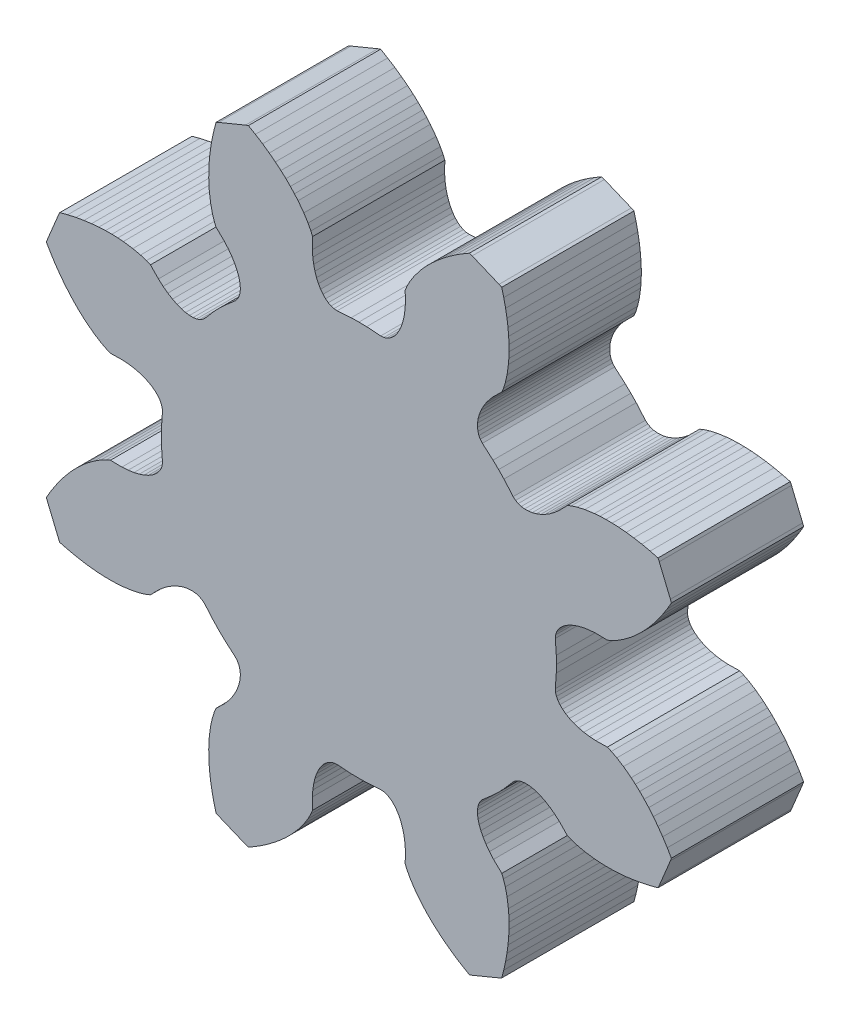
SolidWorks part; units mm, degrees
ref_plane "Front Plane" through (0, 0, 0) normal (0, 0, 1) x (1, 0, 0)
ref_plane "Top Plane" through (0, 0, 0) normal (0, 1, 0) x (1, 0, 0)
ref_plane "Right Plane" through (0, 0, 0) normal (1, 0, 0) x (0, 0, -1)
sketch "Sketch1" plane through (0, 0, 0) normal (0, 0, 1) x (1, 0, 0)
  line L0 (-25.6921, 14.6152) -> (-25.7624, 14.9363)
  line L1 (-25.7624, 14.9363) -> (-25.816, 15.2423)
  line L2 (-25.816, 15.2423) -> (-25.8546, 15.5344)
  line L3 (-25.8546, 15.5344) -> (-25.8795, 15.8113)
  line L4 (-25.8795, 15.8113) -> (-25.892, 16.0716)
  line L5 (-25.892, 16.0716) -> (-25.8935, 16.3157)
  line L6 (-25.8935, 16.3157) -> (-25.8848, 16.5428)
  line L7 (-25.8848, 16.5428) -> (-25.8699, 16.7524)
  line L8 (-25.8699, 16.7524) -> (-25.8175, 17.1189)
  line L9 (-25.8175, 17.1189) -> (-25.7512, 17.4153)
  line L10 (-25.7512, 17.4153) -> (-25.6796, 17.6414)
  line L11 (-25.6796, 17.6414) -> (-25.6164, 17.7971)
  line L12 (-25.6164, 17.7971) -> (-25.2994, 18.1029)
  line L13 (-25.2994, 18.1029) -> (-25.1424, 18.2835)
  line L14 (-25.1424, 18.2835) -> (-25.0085, 18.4641)
  line L15 (-25.0085, 18.4641) -> (-24.8983, 18.6434)
  line L16 (-24.8983, 18.6434) -> (-24.8114, 18.8169)
  line L17 (-24.8114, 18.8169) -> (-24.7469, 18.9835)
  line L18 (-24.7469, 18.9835) -> (-24.7053, 19.1445)
  line L19 (-24.7053, 19.1445) -> (-24.6834, 19.2949)
  line L20 (-24.6834, 19.2949) -> (-24.6819, 19.4371)
  line L21 (-24.6819, 19.4371) -> (-24.7015, 19.5652)
  line L22 (-24.7015, 19.5652) -> (-24.737, 19.681)
  line L23 (-24.737, 19.681) -> (-24.7909, 19.7813)
  line L24 (-24.7909, 19.7813) -> (-24.8706, 19.8766)
  line L25 (-24.8706, 19.8766) -> (-25.2785, 20.2309)
  line L26 (-25.2785, 20.2309) -> (-25.4922, 20.4361)
  line L27 (-25.4922, 20.4361) -> (-25.6976, 20.6495)
  line L28 (-25.6976, 20.6495) -> (-26.0517, 21.0589)
  line L29 (-26.0517, 21.0589) -> (-26.1467, 21.1374)
  line L30 (-26.1467, 21.1374) -> (-26.2476, 21.191)
  line L31 (-26.2476, 21.191) -> (-26.3634, 21.2286)
  line L32 (-26.3634, 21.2286) -> (-26.4927, 21.2461)
  line L33 (-26.4927, 21.2461) -> (-26.6331, 21.2451)
  line L34 (-26.6331, 21.2451) -> (-26.7848, 21.2243)
  line L35 (-26.7848, 21.2243) -> (-26.9445, 21.1816)
  line L36 (-26.9445, 21.1816) -> (-27.1129, 21.1166)
  line L37 (-27.1129, 21.1166) -> (-27.2864, 21.03)
  line L38 (-27.2864, 21.03) -> (-27.4642, 20.9197)
  line L39 (-27.4642, 20.9197) -> (-27.6448, 20.7874)
  line L40 (-27.6448, 20.7874) -> (-27.8267, 20.6287)
  line L41 (-27.8267, 20.6287) -> (-28.1325, 20.3134)
  line L42 (-28.1325, 20.3134) -> (-28.2884, 20.2484)
  line L43 (-28.2884, 20.2484) -> (-28.5143, 20.1783)
  line L44 (-28.5143, 20.1783) -> (-28.8091, 20.111)
  line L45 (-28.8091, 20.111) -> (-29.1757, 20.0597)
  line L46 (-29.1757, 20.0597) -> (-29.3852, 20.0432)
  line L47 (-29.3852, 20.0432) -> (-29.6141, 20.0351)
  line L48 (-29.6141, 20.0351) -> (-29.8579, 20.0363)
  line L49 (-29.8579, 20.0363) -> (-30.1167, 20.0488)
  line L50 (-30.1167, 20.0488) -> (-30.3951, 20.0734)
  line L51 (-30.3951, 20.0734) -> (-30.6862, 20.1138)
  line L52 (-30.6862, 20.1138) -> (-30.9935, 20.1674)
  line L53 (-30.9935, 20.1674) -> (-31.3131, 20.2375)
  line L54 (-31.3131, 20.2375) -> (-31.6148, 20.3162)
  line L55 (-31.6148, 20.3162) -> (-31.6644, 20.4181)
  line L56 (-31.6644, 20.4181) -> (-32.0931, 21.4529)
  line L57 (-32.0931, 21.4529) -> (-32.1302, 21.5575)
  line L58 (-32.1302, 21.5575) -> (-31.9717, 21.8278)
  line L59 (-31.9717, 21.8278) -> (-31.7954, 22.1034)
  line L60 (-31.7954, 22.1034) -> (-31.6161, 22.3584)
  line L61 (-31.6161, 22.3584) -> (-31.4383, 22.5926)
  line L62 (-31.4383, 22.5926) -> (-31.2595, 22.8062)
  line L63 (-31.2595, 22.8062) -> (-31.0845, 22.999)
  line L64 (-31.0845, 22.999) -> (-30.9133, 23.1727)
  line L65 (-30.9133, 23.1727) -> (-30.7467, 23.3272)
  line L66 (-30.7467, 23.3272) -> (-30.5866, 23.4651)
  line L67 (-30.5866, 23.4651) -> (-30.2907, 23.6881)
  line L68 (-30.2907, 23.6881) -> (-30.0342, 23.8494)
  line L69 (-30.0342, 23.8494) -> (-29.8246, 23.9583)
  line L70 (-29.8246, 23.9583) -> (-29.6692, 24.0231)
  line L71 (-29.6692, 24.0231) -> (-29.2295, 24.0163)
  line L72 (-29.2295, 24.0163) -> (-28.9897, 24.0328)
  line L73 (-28.9897, 24.0328) -> (-28.7665, 24.0658)
  line L74 (-28.7665, 24.0658) -> (-28.5638, 24.1138)
  line L75 (-28.5638, 24.1138) -> (-28.3794, 24.176)
  line L76 (-28.3794, 24.176) -> (-28.2153, 24.2489)
  line L77 (-28.2153, 24.2489) -> (-28.0718, 24.332)
  line L78 (-28.0718, 24.332) -> (-27.9494, 24.4239)
  line L79 (-27.9494, 24.4239) -> (-27.8503, 24.5235)
  line L80 (-27.8503, 24.5235) -> (-27.7716, 24.6264)
  line L81 (-27.7716, 24.6264) -> (-27.7152, 24.7341)
  line L82 (-27.7152, 24.7341) -> (-27.6819, 24.8446)
  line L83 (-27.6819, 24.8446) -> (-27.671, 24.967)
  line L84 (-27.671, 24.967) -> (-27.7096, 25.506)
  line L85 (-27.7096, 25.506) -> (-27.7152, 25.8021)
  line L86 (-27.7152, 25.8021) -> (-27.7096, 26.0996)
  line L87 (-27.7096, 26.0996) -> (-27.671, 26.6388)
  line L88 (-27.671, 26.6388) -> (-27.6819, 26.7612)
  line L89 (-27.6819, 26.7612) -> (-27.7152, 26.8715)
  line L90 (-27.7152, 26.8715) -> (-27.7716, 26.9787)
  line L91 (-27.7716, 26.9787) -> (-27.8503, 27.082)
  line L92 (-27.8503, 27.082) -> (-27.9494, 27.1816)
  line L93 (-27.9494, 27.1816) -> (-28.0718, 27.2723)
  line L94 (-28.0718, 27.2723) -> (-28.2153, 27.3566)
  line L95 (-28.2153, 27.3566) -> (-28.3794, 27.4295)
  line L96 (-28.3794, 27.4295) -> (-28.5638, 27.4917)
  line L97 (-28.5638, 27.4917) -> (-28.7665, 27.5397)
  line L98 (-28.7665, 27.5397) -> (-28.9897, 27.5728)
  line L99 (-28.9897, 27.5728) -> (-29.2295, 27.5895)
  line L100 (-29.2295, 27.5895) -> (-29.6692, 27.5824)
  line L101 (-29.6692, 27.5824) -> (-29.8246, 27.6472)
  line L102 (-29.8246, 27.6472) -> (-30.0342, 27.7564)
  line L103 (-30.0342, 27.7564) -> (-30.2907, 27.9174)
  line L104 (-30.2907, 27.9174) -> (-30.5866, 28.1405)
  line L105 (-30.5866, 28.1405) -> (-30.7467, 28.2784)
  line L106 (-30.7467, 28.2784) -> (-30.9133, 28.4328)
  line L107 (-30.9133, 28.4328) -> (-31.0845, 28.6065)
  line L108 (-31.0845, 28.6065) -> (-31.2595, 28.7993)
  line L109 (-31.2595, 28.7993) -> (-31.4383, 29.0129)
  line L110 (-31.4383, 29.0129) -> (-31.6161, 29.2471)
  line L111 (-31.6161, 29.2471) -> (-31.7954, 29.5021)
  line L112 (-31.7954, 29.5021) -> (-31.9717, 29.7777)
  line L113 (-31.9717, 29.7777) -> (-32.1302, 30.048)
  line L114 (-32.1302, 30.048) -> (-32.0931, 30.1537)
  line L115 (-32.0931, 30.1537) -> (-31.6644, 31.1887)
  line L116 (-31.6644, 31.1887) -> (-31.6148, 31.2893)
  line L117 (-31.6148, 31.2893) -> (-31.3131, 31.368)
  line L118 (-31.3131, 31.368) -> (-30.9935, 31.4381)
  line L119 (-30.9935, 31.4381) -> (-30.6862, 31.492)
  line L120 (-30.6862, 31.492) -> (-30.3951, 31.5306)
  line L121 (-30.3951, 31.5306) -> (-30.1167, 31.5568)
  line L122 (-30.1167, 31.5568) -> (-29.8579, 31.5692)
  line L123 (-29.8579, 31.5692) -> (-29.6141, 31.5705)
  line L124 (-29.6141, 31.5705) -> (-29.3852, 31.5623)
  line L125 (-29.3852, 31.5623) -> (-29.1757, 31.5458)
  line L126 (-29.1757, 31.5458) -> (-28.8091, 31.4948)
  line L127 (-28.8091, 31.4948) -> (-28.5143, 31.4272)
  line L128 (-28.5143, 31.4272) -> (-28.2884, 31.3571)
  line L129 (-28.2884, 31.3571) -> (-28.1325, 31.2921)
  line L130 (-28.1325, 31.2921) -> (-27.8267, 30.9764)
  line L131 (-27.8267, 30.9764) -> (-27.6448, 30.8181)
  line L132 (-27.6448, 30.8181) -> (-27.4642, 30.6843)
  line L133 (-27.4642, 30.6843) -> (-27.2864, 30.5758)
  line L134 (-27.2864, 30.5758) -> (-27.1129, 30.4889)
  line L135 (-27.1129, 30.4889) -> (-26.9445, 30.4239)
  line L136 (-26.9445, 30.4239) -> (-26.7848, 30.3812)
  line L137 (-26.7848, 30.3812) -> (-26.6331, 30.3604)
  line L138 (-26.6331, 30.3604) -> (-26.4927, 30.3591)
  line L139 (-26.4927, 30.3591) -> (-26.3634, 30.3772)
  line L140 (-26.3634, 30.3772) -> (-26.2476, 30.4145)
  line L141 (-26.2476, 30.4145) -> (-26.1467, 30.4681)
  line L142 (-26.1467, 30.4681) -> (-26.0517, 30.5469)
  line L143 (-26.0517, 30.5469) -> (-25.6976, 30.956)
  line L144 (-25.6976, 30.956) -> (-25.4922, 31.1694)
  line L145 (-25.4922, 31.1694) -> (-25.2785, 31.3746)
  line L146 (-25.2785, 31.3746) -> (-24.8706, 31.729)
  line L147 (-24.8706, 31.729) -> (-24.7909, 31.8242)
  line L148 (-24.7909, 31.8242) -> (-24.737, 31.9248)
  line L149 (-24.737, 31.9248) -> (-24.7015, 32.0404)
  line L150 (-24.7015, 32.0404) -> (-24.6819, 32.1684)
  line L151 (-24.6819, 32.1684) -> (-24.6834, 32.3094)
  line L152 (-24.6834, 32.3094) -> (-24.7053, 32.461)
  line L153 (-24.7053, 32.461) -> (-24.7469, 32.622)
  line L154 (-24.7469, 32.622) -> (-24.8114, 32.7887)
  line L155 (-24.8114, 32.7887) -> (-24.8983, 32.9621)
  line L156 (-24.8983, 32.9621) -> (-25.0085, 33.1399)
  line L157 (-25.0085, 33.1399) -> (-25.1424, 33.3221)
  line L158 (-25.1424, 33.3221) -> (-25.2994, 33.5026)
  line L159 (-25.2994, 33.5026) -> (-25.6164, 33.8085)
  line L160 (-25.6164, 33.8085) -> (-25.6796, 33.9642)
  line L161 (-25.6796, 33.9642) -> (-25.7512, 34.1902)
  line L162 (-25.7512, 34.1902) -> (-25.8175, 34.4851)
  line L163 (-25.8175, 34.4851) -> (-25.8699, 34.8532)
  line L164 (-25.8699, 34.8532) -> (-25.8848, 35.0627)
  line L165 (-25.8848, 35.0627) -> (-25.8935, 35.2898)
  line L166 (-25.8935, 35.2898) -> (-25.892, 35.5336)
  line L167 (-25.892, 35.5336) -> (-25.8795, 35.7942)
  line L168 (-25.8795, 35.7942) -> (-25.8546, 36.0714)
  line L169 (-25.8546, 36.0714) -> (-25.816, 36.3635)
  line L170 (-25.816, 36.3635) -> (-25.7624, 36.6693)
  line L171 (-25.7624, 36.6693) -> (-25.6921, 36.9903)
  line L172 (-25.6921, 36.9903) -> (-25.6123, 37.2923)
  line L173 (-25.6123, 37.2923) -> (-25.5117, 37.3406)
  line L174 (-25.5117, 37.3406) -> (-24.4767, 37.7688)
  line L175 (-24.4767, 37.7688) -> (-24.3705, 37.8062)
  line L176 (-24.3705, 37.8062) -> (-24.102, 37.6492)
  line L177 (-24.102, 37.6492) -> (-23.8247, 37.4729)
  line L178 (-23.8247, 37.4729) -> (-23.5699, 37.2936)
  line L179 (-23.5699, 37.2936) -> (-23.3372, 37.1145)
  line L180 (-23.3372, 37.1145) -> (-23.1218, 36.9367)
  line L181 (-23.1218, 36.9367) -> (-22.929, 36.7617)
  line L182 (-22.929, 36.7617) -> (-22.7568, 36.5895)
  line L183 (-22.7568, 36.5895) -> (-22.6014, 36.4226)
  line L184 (-22.6014, 36.4226) -> (-22.4632, 36.2629)
  line L185 (-22.4632, 36.2629) -> (-22.2415, 35.968)
  line L186 (-22.2415, 35.968) -> (-22.0789, 35.7114)
  line L187 (-22.0789, 35.7114) -> (-21.9702, 35.5009)
  line L188 (-21.9702, 35.5009) -> (-21.9052, 35.3464)
  line L189 (-21.9052, 35.3464) -> (-21.9123, 34.9052)
  line L190 (-21.9123, 34.9052) -> (-21.8958, 34.6657)
  line L191 (-21.8958, 34.6657) -> (-21.8625, 34.444)
  line L192 (-21.8625, 34.444) -> (-21.8142, 34.2398)
  line L193 (-21.8142, 34.2398) -> (-21.752, 34.0566)
  line L194 (-21.752, 34.0566) -> (-21.6791, 33.8925)
  line L195 (-21.6791, 33.8925) -> (-21.5966, 33.7493)
  line L196 (-21.5966, 33.7493) -> (-21.5041, 33.6266)
  line L197 (-21.5041, 33.6266) -> (-21.4063, 33.526)
  line L198 (-21.4063, 33.526) -> (-21.3017, 33.4473)
  line L199 (-21.3017, 33.4473) -> (-21.194, 33.3922)
  line L200 (-21.194, 33.3922) -> (-21.0853, 33.3591)
  line L201 (-21.0853, 33.3591) -> (-20.9613, 33.3482)
  line L202 (-20.9613, 33.3482) -> (-20.4226, 33.3871)
  line L203 (-20.4226, 33.3871) -> (-20.1262, 33.3922)
  line L204 (-20.1262, 33.3922) -> (-19.8297, 33.3871)
  line L205 (-19.8297, 33.3871) -> (-19.2897, 33.3482)
  line L206 (-19.2897, 33.3482) -> (-19.1671, 33.3591)
  line L207 (-19.1671, 33.3591) -> (-19.0583, 33.3922)
  line L208 (-19.0583, 33.3922) -> (-18.9506, 33.4473)
  line L209 (-18.9506, 33.4473) -> (-18.846, 33.526)
  line L210 (-18.846, 33.526) -> (-18.7467, 33.6266)
  line L211 (-18.7467, 33.6266) -> (-18.6558, 33.7493)
  line L212 (-18.6558, 33.7493) -> (-18.5719, 33.8925)
  line L213 (-18.5719, 33.8925) -> (-18.4988, 34.0566)
  line L214 (-18.4988, 34.0566) -> (-18.4381, 34.2398)
  line L215 (-18.4381, 34.2398) -> (-18.3898, 34.444)
  line L216 (-18.3898, 34.444) -> (-18.3565, 34.6657)
  line L217 (-18.3565, 34.6657) -> (-18.339, 34.9052)
  line L218 (-18.339, 34.9052) -> (-18.3471, 35.3464)
  line L219 (-18.3471, 35.3464) -> (-18.2811, 35.5009)
  line L220 (-18.2811, 35.5009) -> (-18.1721, 35.7114)
  line L221 (-18.1721, 35.7114) -> (-18.0108, 35.968)
  line L222 (-18.0108, 35.968) -> (-17.7876, 36.2629)
  line L223 (-17.7876, 36.2629) -> (-17.6512, 36.4226)
  line L224 (-17.6512, 36.4226) -> (-17.4955, 36.5895)
  line L225 (-17.4955, 36.5895) -> (-17.322, 36.7617)
  line L226 (-17.322, 36.7617) -> (-17.129, 36.9367)
  line L227 (-17.129, 36.9367) -> (-16.9151, 37.1145)
  line L228 (-16.9151, 37.1145) -> (-16.6824, 37.2936)
  line L229 (-16.6824, 37.2936) -> (-16.4277, 37.4729)
  line L230 (-16.4277, 37.4729) -> (-16.1503, 37.6492)
  line L231 (-16.1503, 37.6492) -> (-15.8805, 37.8062)
  line L232 (-15.8805, 37.8062) -> (-15.7756, 37.7688)
  line L233 (-15.7756, 37.7688) -> (-14.7421, 37.3406)
  line L234 (-14.7421, 37.3406) -> (-14.64, 37.2923)
  line L235 (-14.64, 37.2923) -> (-14.5605, 36.9903)
  line L236 (-14.5605, 36.9903) -> (-14.4899, 36.6693)
  line L237 (-14.4899, 36.6693) -> (-14.4363, 36.3635)
  line L238 (-14.4363, 36.3635) -> (-14.3977, 36.0714)
  line L239 (-14.3977, 36.0714) -> (-14.3728, 35.7942)
  line L240 (-14.3728, 35.7942) -> (-14.3591, 35.5336)
  line L241 (-14.3591, 35.5336) -> (-14.3576, 35.2898)
  line L242 (-14.3576, 35.2898) -> (-14.3659, 35.0627)
  line L243 (-14.3659, 35.0627) -> (-14.3827, 34.8532)
  line L244 (-14.3827, 34.8532) -> (-14.4335, 34.4851)
  line L245 (-14.4335, 34.4851) -> (-14.5011, 34.1902)
  line L246 (-14.5011, 34.1902) -> (-14.5727, 33.9642)
  line L247 (-14.5727, 33.9642) -> (-14.6362, 33.8085)
  line L248 (-14.6362, 33.8085) -> (-14.9529, 33.5026)
  line L249 (-14.9529, 33.5026) -> (-15.1099, 33.3221)
  line L250 (-15.1099, 33.3221) -> (-15.2438, 33.1399)
  line L251 (-15.2438, 33.1399) -> (-15.3543, 32.9621)
  line L252 (-15.3543, 32.9621) -> (-15.4409, 32.7887)
  line L253 (-15.4409, 32.7887) -> (-15.5041, 32.622)
  line L254 (-15.5041, 32.622) -> (-15.547, 32.461)
  line L255 (-15.547, 32.461) -> (-15.5689, 32.3094)
  line L256 (-15.5689, 32.3094) -> (-15.5689, 32.1684)
  line L257 (-15.5689, 32.1684) -> (-15.5511, 32.0404)
  line L258 (-15.5511, 32.0404) -> (-15.5153, 31.9248)
  line L259 (-15.5153, 31.9248) -> (-15.4614, 31.8242)
  line L260 (-15.4614, 31.8242) -> (-15.3817, 31.729)
  line L261 (-15.3817, 31.729) -> (-14.9738, 31.3746)
  line L262 (-14.9738, 31.3746) -> (-14.7586, 31.1694)
  line L263 (-14.7586, 31.1694) -> (-14.5534, 30.956)
  line L264 (-14.5534, 30.956) -> (-14.1991, 30.5469)
  line L265 (-14.1991, 30.5469) -> (-14.1056, 30.4681)
  line L266 (-14.1056, 30.4681) -> (-14.0037, 30.4145)
  line L267 (-14.0037, 30.4145) -> (-13.8877, 30.3772)
  line L268 (-13.8877, 30.3772) -> (-13.7596, 30.3591)
  line L269 (-13.7596, 30.3591) -> (-13.6192, 30.3604)
  line L270 (-13.6192, 30.3604) -> (-13.4675, 30.3812)
  line L271 (-13.4675, 30.3812) -> (-13.3078, 30.4239)
  line L272 (-13.3078, 30.4239) -> (-13.1394, 30.4889)
  line L273 (-13.1394, 30.4889) -> (-12.9659, 30.5758)
  line L274 (-12.9659, 30.5758) -> (-12.7881, 30.6843)
  line L275 (-12.7881, 30.6843) -> (-12.6078, 30.8181)
  line L276 (-12.6078, 30.8181) -> (-12.4256, 30.9764)
  line L277 (-12.4256, 30.9764) -> (-12.1198, 31.2921)
  line L278 (-12.1198, 31.2921) -> (-11.9639, 31.3571)
  line L279 (-11.9639, 31.3571) -> (-11.7381, 31.4272)
  line L280 (-11.7381, 31.4272) -> (-11.4432, 31.4948)
  line L281 (-11.4432, 31.4948) -> (-11.0766, 31.5458)
  line L282 (-11.0766, 31.5458) -> (-10.8658, 31.5623)
  line L283 (-10.8658, 31.5623) -> (-10.6382, 31.5705)
  line L284 (-10.6382, 31.5705) -> (-10.3944, 31.5692)
  line L285 (-10.3944, 31.5692) -> (-10.1341, 31.5568)
  line L286 (-10.1341, 31.5568) -> (-9.8572, 31.5306)
  line L287 (-9.8572, 31.5306) -> (-9.5651, 31.492)
  line L288 (-9.5651, 31.492) -> (-9.2588, 31.4381)
  line L289 (-9.2588, 31.4381) -> (-8.9377, 31.368)
  line L290 (-8.9377, 31.368) -> (-8.6362, 31.2893)
  line L291 (-8.6362, 31.2893) -> (-8.588, 31.1887)
  line L292 (-8.588, 31.1887) -> (-8.1592, 30.1537)
  line L293 (-8.1592, 30.1537) -> (-8.1221, 30.048)
  line L294 (-8.1221, 30.048) -> (-8.2791, 29.7777)
  line L295 (-8.2791, 29.7777) -> (-8.4569, 29.5021)
  line L296 (-8.4569, 29.5021) -> (-8.6347, 29.2471)
  line L297 (-8.6347, 29.2471) -> (-8.814, 29.0129)
  line L298 (-8.814, 29.0129) -> (-8.9928, 28.7993)
  line L299 (-8.9928, 28.7993) -> (-9.1681, 28.6065)
  line L300 (-9.1681, 28.6065) -> (-9.339, 28.4328)
  line L301 (-9.339, 28.4328) -> (-9.5059, 28.2784)
  line L302 (-9.5059, 28.2784) -> (-9.6657, 28.1405)
  line L303 (-9.6657, 28.1405) -> (-9.9618, 27.9174)
  line L304 (-9.9618, 27.9174) -> (-10.2166, 27.7564)
  line L305 (-10.2166, 27.7564) -> (-10.4277, 27.6472)
  line L306 (-10.4277, 27.6472) -> (-10.5831, 27.5824)
  line L307 (-10.5831, 27.5824) -> (-11.0228, 27.5895)
  line L308 (-11.0228, 27.5895) -> (-11.2626, 27.5728)
  line L309 (-11.2626, 27.5728) -> (-11.4846, 27.5397)
  line L310 (-11.4846, 27.5397) -> (-11.6885, 27.4917)
  line L311 (-11.6885, 27.4917) -> (-11.8729, 27.4295)
  line L312 (-11.8729, 27.4295) -> (-12.037, 27.3566)
  line L313 (-12.037, 27.3566) -> (-12.1805, 27.2723)
  line L314 (-12.1805, 27.2723) -> (-12.3014, 27.1816)
  line L315 (-12.3014, 27.1816) -> (-12.402, 27.082)
  line L316 (-12.402, 27.082) -> (-12.4808, 26.9787)
  line L317 (-12.4808, 26.9787) -> (-12.5359, 26.8715)
  line L318 (-12.5359, 26.8715) -> (-12.5704, 26.7612)
  line L319 (-12.5704, 26.7612) -> (-12.5813, 26.6388)
  line L320 (-12.5813, 26.6388) -> (-12.5427, 26.0996)
  line L321 (-12.5427, 26.0996) -> (-12.5359, 25.8021)
  line L322 (-12.5359, 25.8021) -> (-12.5427, 25.506)
  line L323 (-12.5427, 25.506) -> (-12.5813, 24.967)
  line L324 (-12.5813, 24.967) -> (-12.5704, 24.8446)
  line L325 (-12.5704, 24.8446) -> (-12.5359, 24.7341)
  line L326 (-12.5359, 24.7341) -> (-12.4808, 24.6264)
  line L327 (-12.4808, 24.6264) -> (-12.402, 24.5235)
  line L328 (-12.402, 24.5235) -> (-12.3014, 24.4239)
  line L329 (-12.3014, 24.4239) -> (-12.1805, 24.332)
  line L330 (-12.1805, 24.332) -> (-12.037, 24.2489)
  line L331 (-12.037, 24.2489) -> (-11.8729, 24.176)
  line L332 (-11.8729, 24.176) -> (-11.6885, 24.1138)
  line L333 (-11.6885, 24.1138) -> (-11.4846, 24.0658)
  line L334 (-11.4846, 24.0658) -> (-11.2626, 24.0328)
  line L335 (-11.2626, 24.0328) -> (-11.0228, 24.0163)
  line L336 (-11.0228, 24.0163) -> (-10.5831, 24.0231)
  line L337 (-10.5831, 24.0231) -> (-10.4277, 23.9583)
  line L338 (-10.4277, 23.9583) -> (-10.2166, 23.8494)
  line L339 (-10.2166, 23.8494) -> (-9.9618, 23.6881)
  line L340 (-9.9618, 23.6881) -> (-9.6657, 23.4651)
  line L341 (-9.6657, 23.4651) -> (-9.5059, 23.3272)
  line L342 (-9.5059, 23.3272) -> (-9.339, 23.1727)
  line L343 (-9.339, 23.1727) -> (-9.1681, 22.999)
  line L344 (-9.1681, 22.999) -> (-8.9928, 22.8062)
  line L345 (-8.9928, 22.8062) -> (-8.814, 22.5926)
  line L346 (-8.814, 22.5926) -> (-8.6347, 22.3584)
  line L347 (-8.6347, 22.3584) -> (-8.4569, 22.1034)
  line L348 (-8.4569, 22.1034) -> (-8.2791, 21.8278)
  line L349 (-8.2791, 21.8278) -> (-8.1221, 21.5575)
  line L350 (-8.1221, 21.5575) -> (-8.1592, 21.4529)
  line L351 (-8.1592, 21.4529) -> (-8.588, 20.4181)
  line L352 (-8.588, 20.4181) -> (-8.6362, 20.3162)
  line L353 (-8.6362, 20.3162) -> (-8.9377, 20.2375)
  line L354 (-8.9377, 20.2375) -> (-9.2588, 20.1674)
  line L355 (-9.2588, 20.1674) -> (-9.5651, 20.1138)
  line L356 (-9.5651, 20.1138) -> (-9.8572, 20.0734)
  line L357 (-9.8572, 20.0734) -> (-10.1341, 20.0488)
  line L358 (-10.1341, 20.0488) -> (-10.3944, 20.0363)
  line L359 (-10.3944, 20.0363) -> (-10.6382, 20.0351)
  line L360 (-10.6382, 20.0351) -> (-10.8658, 20.0432)
  line L361 (-10.8658, 20.0432) -> (-11.0766, 20.0597)
  line L362 (-11.0766, 20.0597) -> (-11.4432, 20.111)
  line L363 (-11.4432, 20.111) -> (-11.7381, 20.1783)
  line L364 (-11.7381, 20.1783) -> (-11.9639, 20.2484)
  line L365 (-11.9639, 20.2484) -> (-12.1198, 20.3134)
  line L366 (-12.1198, 20.3134) -> (-12.4256, 20.6287)
  line L367 (-12.4256, 20.6287) -> (-12.6078, 20.7874)
  line L368 (-12.6078, 20.7874) -> (-12.7881, 20.9197)
  line L369 (-12.7881, 20.9197) -> (-12.9659, 21.03)
  line L370 (-12.9659, 21.03) -> (-13.1394, 21.1166)
  line L371 (-13.1394, 21.1166) -> (-13.3078, 21.1816)
  line L372 (-13.3078, 21.1816) -> (-13.4675, 21.2243)
  line L373 (-13.4675, 21.2243) -> (-13.6192, 21.2451)
  line L374 (-13.6192, 21.2451) -> (-13.7596, 21.2461)
  line L375 (-13.7596, 21.2461) -> (-13.8877, 21.2286)
  line L376 (-13.8877, 21.2286) -> (-14.0037, 21.191)
  line L377 (-14.0037, 21.191) -> (-14.1056, 21.1374)
  line L378 (-14.1056, 21.1374) -> (-14.1991, 21.0589)
  line L379 (-14.1991, 21.0589) -> (-14.5534, 20.6495)
  line L380 (-14.5534, 20.6495) -> (-14.7586, 20.4361)
  line L381 (-14.7586, 20.4361) -> (-14.9738, 20.2309)
  line L382 (-14.9738, 20.2309) -> (-15.3817, 19.8766)
  line L383 (-15.3817, 19.8766) -> (-15.4614, 19.7813)
  line L384 (-15.4614, 19.7813) -> (-15.5153, 19.681)
  line L385 (-15.5153, 19.681) -> (-15.5511, 19.5652)
  line L386 (-15.5511, 19.5652) -> (-15.5689, 19.4371)
  line L387 (-15.5689, 19.4371) -> (-15.5689, 19.2949)
  line L388 (-15.5689, 19.2949) -> (-15.547, 19.1445)
  line L389 (-15.547, 19.1445) -> (-15.5041, 18.9835)
  line L390 (-15.5041, 18.9835) -> (-15.4409, 18.8169)
  line L391 (-15.4409, 18.8169) -> (-15.3543, 18.6434)
  line L392 (-15.3543, 18.6434) -> (-15.2438, 18.4641)
  line L393 (-15.2438, 18.4641) -> (-15.1099, 18.2835)
  line L394 (-15.1099, 18.2835) -> (-14.9529, 18.1029)
  line L395 (-14.9529, 18.1029) -> (-14.6362, 17.7971)
  line L396 (-14.6362, 17.7971) -> (-14.5727, 17.6414)
  line L397 (-14.5727, 17.6414) -> (-14.5011, 17.4153)
  line L398 (-14.5011, 17.4153) -> (-14.4335, 17.1189)
  line L399 (-14.4335, 17.1189) -> (-14.3827, 16.7524)
  line L400 (-14.3827, 16.7524) -> (-14.3659, 16.5428)
  line L401 (-14.3659, 16.5428) -> (-14.3576, 16.3157)
  line L402 (-14.3576, 16.3157) -> (-14.3591, 16.0716)
  line L403 (-14.3591, 16.0716) -> (-14.3728, 15.8113)
  line L404 (-14.3728, 15.8113) -> (-14.3977, 15.5344)
  line L405 (-14.3977, 15.5344) -> (-14.4363, 15.2423)
  line L406 (-14.4363, 15.2423) -> (-14.4899, 14.9363)
  line L407 (-14.4899, 14.9363) -> (-14.5605, 14.6152)
  line L408 (-14.5605, 14.6152) -> (-14.64, 14.3135)
  line L409 (-14.64, 14.3135) -> (-14.7421, 14.2649)
  line L410 (-14.7421, 14.2649) -> (-15.7756, 13.8367)
  line L411 (-15.7756, 13.8367) -> (-15.8805, 13.7994)
  line L412 (-15.8805, 13.7994) -> (-16.1503, 13.9563)
  line L413 (-16.1503, 13.9563) -> (-16.4277, 14.1326)
  line L414 (-16.4277, 14.1326) -> (-16.6824, 14.3119)
  line L415 (-16.6824, 14.3119) -> (-16.9151, 14.4913)
  line L416 (-16.9151, 14.4913) -> (-17.129, 14.6691)
  line L417 (-17.129, 14.6691) -> (-17.322, 14.8438)
  line L418 (-17.322, 14.8438) -> (-17.4955, 15.016)
  line L419 (-17.4955, 15.016) -> (-17.6512, 15.1829)
  line L420 (-17.6512, 15.1829) -> (-17.7876, 15.3427)
  line L421 (-17.7876, 15.3427) -> (-18.0108, 15.6376)
  line L422 (-18.0108, 15.6376) -> (-18.1721, 15.8941)
  line L423 (-18.1721, 15.8941) -> (-18.2811, 16.1047)
  line L424 (-18.2811, 16.1047) -> (-18.3471, 16.2594)
  line L425 (-18.3471, 16.2594) -> (-18.339, 16.7003)
  line L426 (-18.339, 16.7003) -> (-18.3565, 16.9398)
  line L427 (-18.3565, 16.9398) -> (-18.3898, 17.1616)
  line L428 (-18.3898, 17.1616) -> (-18.4381, 17.3655)
  line L429 (-18.4381, 17.3655) -> (-18.4988, 17.5489)
  line L430 (-18.4988, 17.5489) -> (-18.5719, 17.713)
  line L431 (-18.5719, 17.713) -> (-18.6558, 17.8562)
  line L432 (-18.6558, 17.8562) -> (-18.7467, 17.9789)
  line L433 (-18.7467, 17.9789) -> (-18.846, 18.0795)
  line L434 (-18.846, 18.0795) -> (-18.9506, 18.1567)
  line L435 (-18.9506, 18.1567) -> (-19.0583, 18.2134)
  line L436 (-19.0583, 18.2134) -> (-19.1671, 18.2464)
  line L437 (-19.1671, 18.2464) -> (-19.2897, 18.2573)
  line L438 (-19.2897, 18.2573) -> (-19.8297, 18.2187)
  line L439 (-19.8297, 18.2187) -> (-20.1262, 18.2134)
  line L440 (-20.1262, 18.2134) -> (-20.4226, 18.2187)
  line L441 (-20.4226, 18.2187) -> (-20.9613, 18.2573)
  line L442 (-20.9613, 18.2573) -> (-21.0853, 18.2464)
  line L443 (-21.0853, 18.2464) -> (-21.194, 18.2134)
  line L444 (-21.194, 18.2134) -> (-21.3017, 18.1567)
  line L445 (-21.3017, 18.1567) -> (-21.4063, 18.0795)
  line L446 (-21.4063, 18.0795) -> (-21.5041, 17.9789)
  line L447 (-21.5041, 17.9789) -> (-21.5966, 17.8562)
  line L448 (-21.5966, 17.8562) -> (-21.6791, 17.713)
  line L449 (-21.6791, 17.713) -> (-21.752, 17.5489)
  line L450 (-21.752, 17.5489) -> (-21.8142, 17.3655)
  line L451 (-21.8142, 17.3655) -> (-21.8625, 17.1616)
  line L452 (-21.8625, 17.1616) -> (-21.8958, 16.9398)
  line L453 (-21.8958, 16.9398) -> (-21.9123, 16.7003)
  line L454 (-21.9123, 16.7003) -> (-21.9052, 16.2594)
  line L455 (-21.9052, 16.2594) -> (-21.9702, 16.1047)
  line L456 (-21.9702, 16.1047) -> (-22.0789, 15.8941)
  line L457 (-22.0789, 15.8941) -> (-22.2415, 15.6376)
  line L458 (-22.2415, 15.6376) -> (-22.4632, 15.3427)
  line L459 (-22.4632, 15.3427) -> (-22.6014, 15.1829)
  line L460 (-22.6014, 15.1829) -> (-22.7568, 15.016)
  line L461 (-22.7568, 15.016) -> (-22.929, 14.8438)
  line L462 (-22.929, 14.8438) -> (-23.1218, 14.6691)
  line L463 (-23.1218, 14.6691) -> (-23.3372, 14.4913)
  line L464 (-23.3372, 14.4913) -> (-23.5699, 14.3119)
  line L465 (-23.5699, 14.3119) -> (-23.8247, 14.1326)
  line L466 (-23.8247, 14.1326) -> (-24.102, 13.9563)
  line L467 (-24.102, 13.9563) -> (-24.3705, 13.7994)
  line L468 (-24.3705, 13.7994) -> (-24.4767, 13.8367)
  line L469 (-24.4767, 13.8367) -> (-25.5117, 14.2649)
  line L470 (-25.5117, 14.2649) -> (-25.6123, 14.3135)
  line L471 (-25.6123, 14.3135) -> (-25.6921, 14.6152)
  point P472 (0, 0)
extrude "Boss-Extrude1" add sketch "Sketch1" along normal blind 5.08
